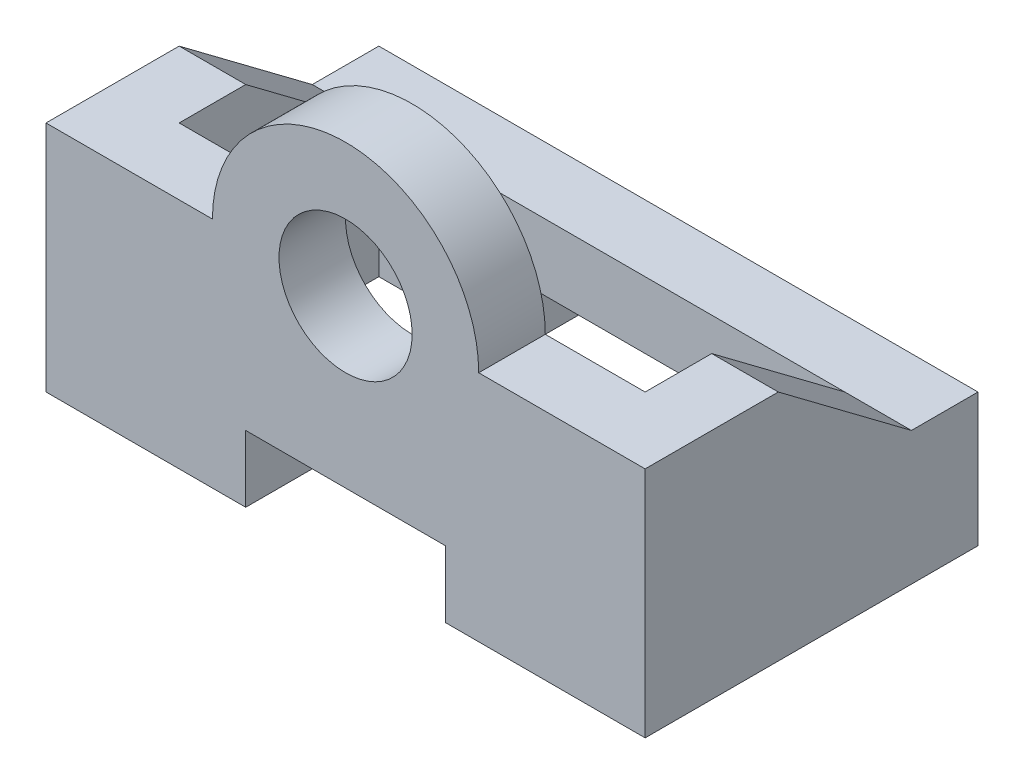
SolidWorks part; units mm, degrees
ref_plane "Front Plane" through (0, 0, 0) normal (0, 0, 1) x (1, 0, 0)
ref_plane "Top Plane" through (0, 0, 0) normal (0, 1, 0) x (1, 0, 0)
ref_plane "Right Plane" through (0, 0, 0) normal (1, 0, 0) x (0, 0, -1)
other "Center of Mass"
sketch "Sketch1" plane through (0, 0, 0) normal (0, 0, 1) x (1, 0, 0)
  line L0 (0, 0) -> (0, 27.5) construction
  line L1 (0, 0) -> (0, -27.5) construction
  line L2 (0, 0) -> (-45, 0) construction
  line L3 (0, 0) -> (45, 0) construction
  line L4 (-45, -27.5) -> (-15, -27.5)
  line L5 (45, -27.5) -> (15, -27.5)
  line L6 (-45, -27.5) -> (-45, -7.5)
  line L7 (45, -27.5) -> (45, -7.5)
  line L8 (-45, -7.5) -> (45, -7.5)
  line L9 (-15, -27.5) -> (-15, -17.5)
  line L10 (15, -27.5) -> (15, -17.5)
  line L11 (-15, -17.5) -> (15, -17.5)
  dimension "D1" = 20
  dimension "D2" = 30
  dimension "D3" = 30
  dimension "D4" = 90
extrude "Boss-Extrude1" add sketch "Sketch1" along normal blind 10
sketch "Sketch2" plane through (0, 0, 0) normal (1, 0, 0) x (0, 0, -1)
  line L0 (0, -27.5) -> (-50, -27.5)
  line L1 (-50, -27.5) -> (-50, 7.5)
  line L2 (-50, 7.5) -> (-30, 7.5)
  line L3 (-30, 7.5) -> (-10, -7.5)
  line L5 (-10, -7.5) -> (-40, -7.5) construction
  line L6 (-50, -7.5) -> (-40, -7.5) construction
  line L11 (0, -27.5) -> (0, -7.5)
  line L12 (0, -7.5) -> (-10, -7.5)
  line L13 (-10, -7.5) -> (-10, -27.5)
  line L14 (-10, -27.5) -> (0, -27.5)
  line L15 (0, -27.5) -> (0, -7.5)
  line L16 (0, -7.5) -> (-10, -7.5)
  dimension "D1" = 30
  dimension "D2" = 10
  dimension "D3" = 20
  dimension "D4" = 35
  dimension "D6" = 0
extrude "Boss-Extrude2" add sketch "Sketch2" along normal mid plane 10 separate body
sketch "Sketch3" plane through (0, 0, 0) normal (0, 0, 1) x (1, 0, 0)
  line L0 (-5, -27.5) -> (-15, -27.5) construction
  line L2 (-15, -27.5) -> (-45, -27.5)
  line L3 (-45, -27.5) -> (-45, 7.5)
  line L4 (-45, 7.5) -> (45, 7.5)
  line L5 (45, 7.5) -> (45, -27.5)
  line L6 (45, -27.5) -> (15, -27.5)
  line L7 (15, -27.5) -> (15, -17.5)
  line L8 (15, -17.5) -> (-15, -17.5)
  line L9 (-15, -17.5) -> (-15, -27.5)
  circle A0 centre (0, 7.5) radius 20
  circle A1 centre (0, 7.5) radius 10
  dimension "D1" = 20
  dimension "D2" = 40
  dimension "D3" = 90
  dimension "D7" = 35
extrude "Boss-Extrude3" add sketch "Sketch3" against normal blind 10 separate body contours A0 L4 L3 L2 L9 L8 L7 L6 L5 | A1 L4 A0 | A1 L4 A0
move or copy body "Body-Move/Copy1" bodies to move or copy 103 copy no translate (0, 0, 50)
move or copy body "Body-Move/Copy2" bodies to move or copy 102 copy no translate (40, 0, 0)
move or copy body "Body-Move/Copy3" bodies to move or copy 105 copy yes number of copies 1 translate (-80, 0, 0)
combine bodies "Combine1" operation type add bodies to combine 105 104 106 101
move or copy body "Body-Move/Copy5" bodies to move or copy 107 copy no translate (0, 0, -25)
